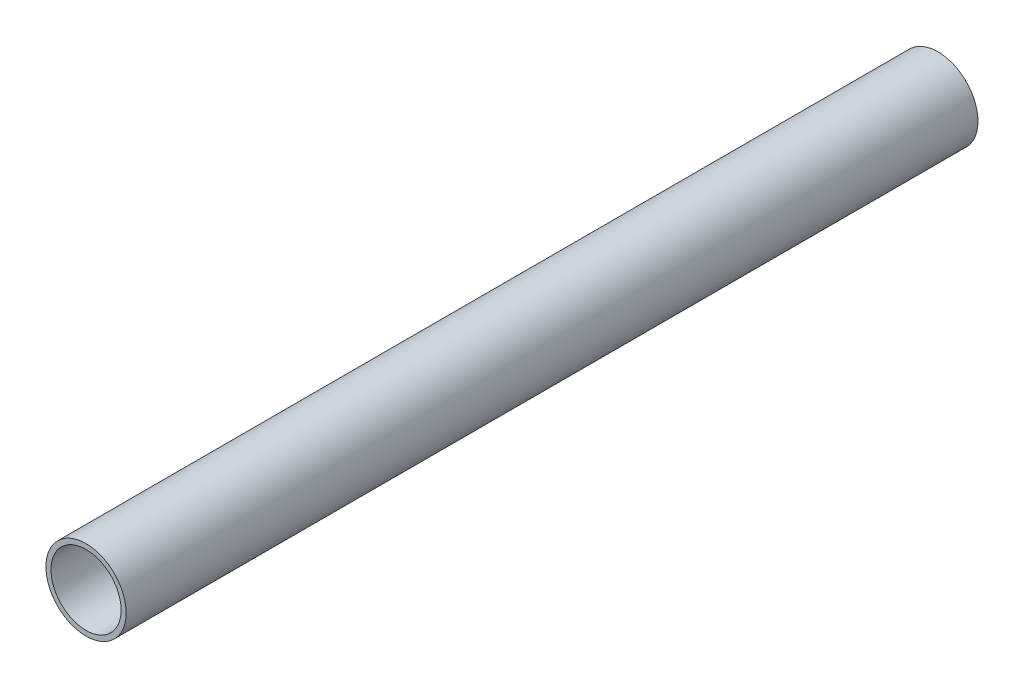
SolidWorks part; units mm, degrees
material "PC High Viscosity"
ref_plane "Front Plane" through (0, 0, 0) normal (0, 0, 1) x (1, 0, 0)
ref_plane "Top Plane" through (0, 0, 0) normal (0, 1, 0) x (1, 0, 0)
ref_plane "Right Plane" through (0, 0, 0) normal (1, 0, 0) x (0, 0, -1)
sketch "Sketch1" plane through (0, 0, 0) normal (0, 0, 1) x (1, 0, 0)
  circle A0 centre (0, 0) radius 22.225
  circle A1 centre (0, 0) radius 25.4
  dimension "D1" = 50.8
  dimension "D2" = 44.45
extrude "Boss-Extrude1" add sketch "Sketch1" along normal mid plane 539.7881
